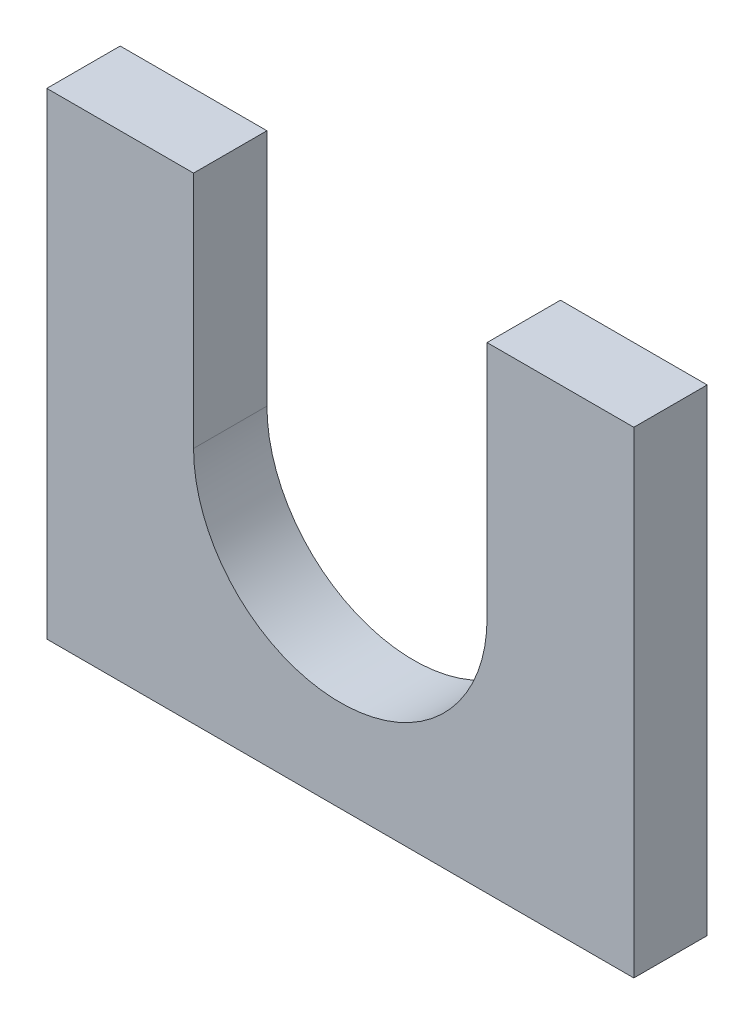
SolidWorks part; units mm, degrees
ref_plane "Alzado" through (0, 0, 0) normal (0, 0, 1) x (1, 0, 0)
ref_plane "Planta" through (0, 0, 0) normal (0, 1, 0) x (1, 0, 0)
ref_plane "Vista lateral" through (0, 0, 0) normal (1, 0, 0) x (0, 0, -1)
sketch "Croquis1" plane through (0, 0, 0) normal (0, 1, 0) x (1, 0, 0)
  line L1 (0, 0) -> (16, 0)
  line L2 (0, 0) -> (0, 2)
  line L3 (0, 2) -> (16, 2)
  line L4 (16, 0) -> (16, 2)
  dimension "D1" = 2
  dimension "D2" = 16
extrude "Saliente-Extruir1" add sketch "Croquis1" along normal blind 13
sketch "Croquis2" plane through (0, 0, -2) normal (0, 0, -1) x (-1, 0, 0)
  line L0 (0, 13) -> (0, 6.5) construction
  line L1 (0, 13) -> (0, 0) construction
  line L2 (0, 6.5) -> (-8, 6.5) construction
  line L4 (-4, 6.5) -> (-4, 13)
  line L5 (-16, 13) -> (0, 13) construction
  line L6 (-4, 13) -> (-12, 13)
  line L7 (-12, 13) -> (-12, 6.5)
  arc A1 (-4, 6.5) -> (-12, 6.5) centre (-8, 6.5) cw
  dimension "D2" = 4
  dimension "D1" = 8
extrude "Cortar-Extruir1" cut sketch "Croquis2" against normal through all
